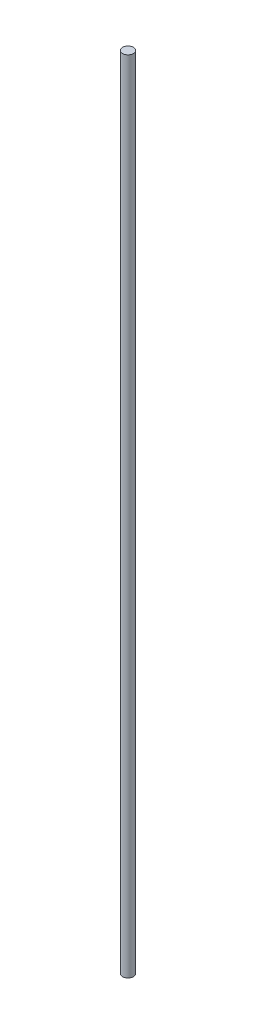
SolidWorks part; units mm, degrees
material "合金钢"
ref_plane "前视基准面" through (0, 0, 0) normal (0, 0, 1) x (1, 0, 0)
ref_plane "上视基准面" through (0, 0, 0) normal (0, 1, 0) x (1, 0, 0)
ref_plane "右视基准面" through (0, 0, 0) normal (1, 0, 0) x (0, 0, -1)
sketch "草图1" plane through (0, 0, 0) normal (0, 1, 0) x (1, 0, 0)
  circle A0 centre (0, 0) radius 4
  dimension "D1" = 8
extrude "凸台-拉伸1" add sketch "草图1" along normal blind 590
cosmetic thread "装饰螺纹线1" parameters "D2"=7
